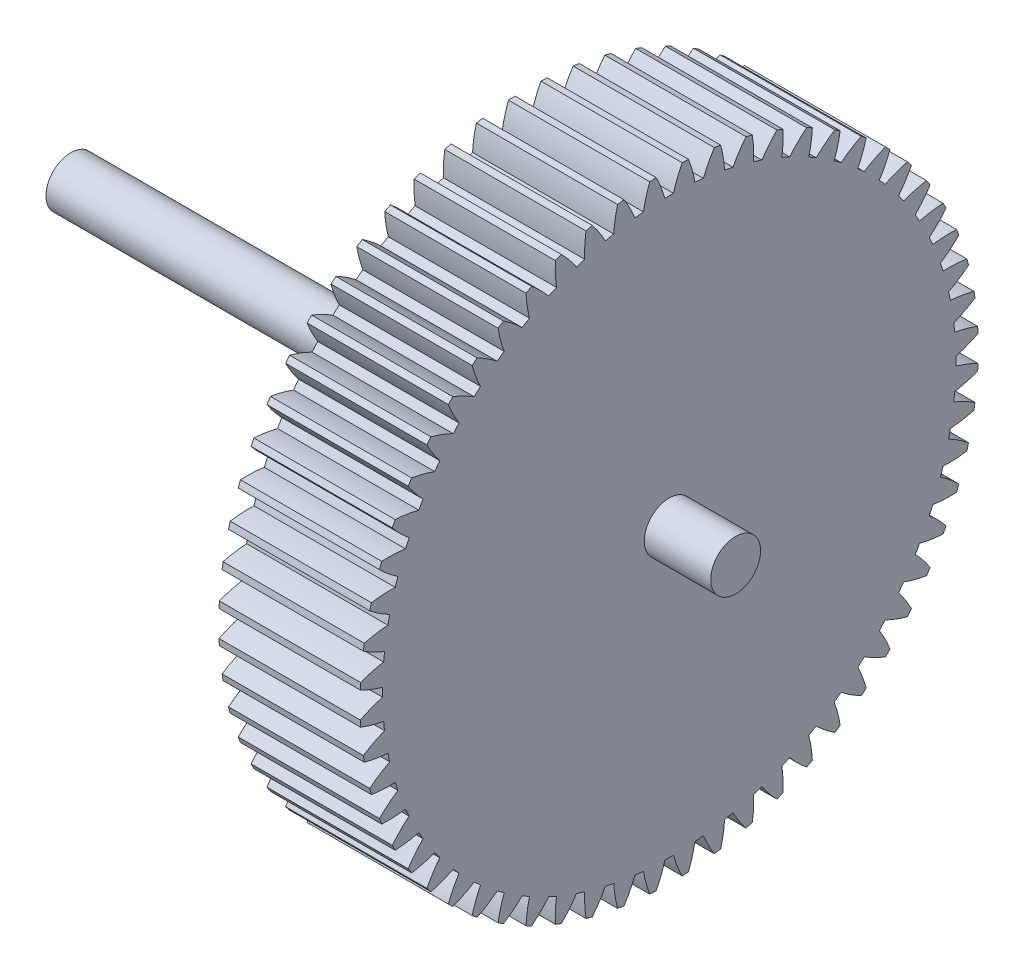
SolidWorks part; units mm, degrees
ref_plane "Plane1" through (0, 0, 0) normal (0, 0, 1) x (1, 0, 0)
ref_plane "Plane2" through (0, 0, 0) normal (0, 1, 0) x (1, 0, 0)
ref_plane "Plane3" through (0, 0, 0) normal (1, 0, 0) x (0, 0, -1)
sketch "HoldingSke" plane through (0, 0, 0) normal (0, 1, 0) x (1, 0, 0)
  line L0 (0, 0) -> (0.8333, -1.4434)
  line L1 (-15, 0) -> (100, 0) construction
  line L2 (0, 0) -> (-2.1039, 2.3779)
  line L3 (0, 0) -> (-11.863, 4.5341)
  line L4 (0, 0) -> (4.318, 7.479)
  line L5 (0, 0) -> (-46.8476, -17.4728)
  line L6 (0, 0) -> (-7.0462, -4.7541)
  line L7 (-2.1039, 2.3779) -> (8.6586, 51.2059)
  line L8 (-76.2, 54.61) -> (-75.9, 54.61)
  line L9 (-71.009, 38.7566) -> (-53.1078, 45.2721)
  line L10 (-76.2, 71.12) -> (104.1128, 71.12)
  line L11 (0, 0) -> (-8.5, 0)
  line L12 (-76.2, 101.6) -> (-76.177, 101.6)
  line L13 (24.9733, 27.94) -> (52.9518, 28.4284)
  line L14 (24.9733, 27.94) -> (24.9743, 27.94)
  line L15 (24.9733, 27.94) -> (100.4006, 29.5858)
  line L16 (-63.627, -0.6) -> (-12.827, -0.6)
  circle A0 centre (0, 0) radius 1
  circle A1 centre (0, 0) radius 17.249
  circle A2 centre (0, 0) radius 37.5
  circle A3 centre (0, 0) radius 1
  dimension "MHD" = 34.498
  dimension "Hub_dia" = 75
  dimension "Bore" = 2
  dimension "MBD" = 2
  dimension "Num_teeth" = 60
  dimension "Pitch" = 1.6667
  dimension "Overall_len" = 50
  dimension "Show_teeth" = 60
  dimension "Thickness" = 8.5
  dimension "OAL" = 50.0001
  dimension "T_dim" = 0.3
  dimension "Ap" = 20
  dimension "H" = 19.05
  dimension "Pitch_radius" = 180.3128
  dimension "Width" = 8.5
  dimension "Backlash" = 0.023
  dimension "Addendum_fac" = 1
  dimension "Dedendum_fac" = 1.25
  dimension "Clearance_fac" = 0.25
  dimension "Dedendum_add" = 0.001
  dimension "Module" = 0.6
sketch "BasProSke" plane through (0, 0, 0) normal (0, 1, 0) x (1, 0, 0)
  line L0 (-10, 0) -> (60, 0) construction
  line L1 (0, 0) -> (0, 18.6)
  line L2 (0, 0) -> (8.5, 0)
  line L3 (8.5, 0) -> (8.5, 18.6)
  line L4 (8.5, 18.6) -> (0, 18.6)
  dimension "Thickness" = 8.5
  dimension "Diameter" = 37.2
revolve "Base-Revolve" add sketch "BasProSke" angle 360 about L0
sketch "TooCutSke" plane through (0, 0, 0) normal (1, 0, 0) x (0, 0, -1)
  line L1 (0, 0) -> (0, 107) construction
  line L2 (0, 0) -> (-0.5114, 17.9927) construction
  line L3 (0, 0) -> (-1.8836, 35.9404) construction
  line L4 (-0.5114, 17.9927) -> (-0.9418, 17.9702) construction
  arc A0 (0.2583, 17.2471) -> (-0.2583, 17.2471) centre (0, 0) ccw
  arc A1 (0.7931, 18.6085) -> (-0.7931, 18.6085) centre (0, 0) ccw
  circle A2 centre (0, 0) radius 18 construction
  circle A3 centre (0, 0) radius 16.9145 construction
  arc A4 (-0.2583, 17.2471) -> (-0.7931, 18.6085) centre (-7.1926, 15.309) ccw
  arc A5 (0.7931, 18.6085) -> (0.2583, 17.2471) centre (7.1926, 15.309) ccw
  dimension "Root_dia" = 34.498
  dimension "Overcut_dia" = 37.2508
  dimension "Pitch_dia" = 36
  dimension "Base_dia" = 33.8289
  dimension "Flank_rad" = 7.2
  dimension "Half_ang" = 3
  dimension "Half_CT" = 0.4309
extrude "ToothCut" cut sketch "TooCutSke" along normal through all
fillet "Breaks" [suppressed] radius 0.012
fillet "RootFillets" [suppressed] radius 0.151
pattern_circular "TeethCuts" count 60 every 6 about axis through (-10, 0, 0) along (1, 0, 0) of "ToothCut", "RootFillets", "Breaks"
sketch "HubNeaOneSke" plane through (0, 0, 0) normal (-1, 0, 0) x (0, 0, 1)
  circle A0 centre (0, 0) radius 17.249
  dimension "Diameter" = 34.498
extrude "HubNearOne" [suppressed] add sketch "HubNeaOneSke" along normal blind 41.5001
sketch "HubNeaBotSke" plane through (0, 0, 0) normal (-1, 0, 0) x (0, 0, 1)
  circle A0 centre (0, 0) radius 17.249
  dimension "Diameter" = 34.498
extrude "HubNearBoth" [suppressed] add sketch "HubNeaBotSke" along normal blind 20.75
ref_plane "FarPln" through (8.5, 0, 0) normal (1, 0, 0) x (0, 0, -1)
sketch "HubFarSke" plane through (8.5, 0, 0) normal (1, 0, 0) x (0, 0, -1)
  circle A0 centre (0, 0) radius 17.249
  dimension "Diameter" = 34.498
extrude "HubFar" [suppressed] add sketch "HubFarSke" along normal blind 20.75
sketch "BorSke" plane through (0, 0, 0) normal (1, 0, 0) x (0, 0, -1)
  circle A0 centre (0, 0) radius 1
  dimension "Diameter" = 2
extrude "Bore" cut sketch "BorSke" along normal mid plane 100.0001
sketch "KeySke" plane through (0, 0, 0) normal (1, 0, 0) x (0, 0, -1)
  line L0 (-0.4, 0) -> (-0.4, 1.3)
  line L1 (-0.4, 1.3) -> (0.4, 1.3)
  line L2 (0.4, 1.3) -> (0.4, 0)
  line L3 (0, 0) -> (0, 34) construction
  line L4 (-0.4, 0) -> (0.4, 0)
  dimension "Offset" = 1.3
  dimension "Width" = 0.8
extrude "Keyway" [suppressed] cut sketch "KeySke" along normal mid plane 100.0001
pattern_circular "Keyway2" [suppressed] count 2 every 90 about axis through (-10, 0, 0) along (1, 0, 0)
sketch "Skizze1" plane through (8.5, 0, 0) normal (1, 0, 0) x (0, 0, -1)
  circle A0 centre (0, 0) radius 1.5
  dimension "D1" = 3
extrude "Aufsatz-Linear austragen1" add sketch "Skizze1" along normal blind 4 and the other way blind 36
equation "' \"Module@HoldingSke\" = 6.35"
equation "' \"Num_teeth@HoldingSke\" = 12"
equation "' \"Ap@HoldingSke\" =  20"
equation "' \"Ap@HoldingSke\" = 20"
equation "' \"Width@HoldingSke\" = 0.5 * 25.4"
equation "' \"Hub_dia@HoldingSke\"= 1 * 25.4"
equation "' \"Hub_dia@HoldingSke\" = 1 * 25.4"
equation "' \"Overall_len@HoldingSke\" = 1.0 * 25.4"
equation "' \"Bore@HoldingSke\" = 0.75 * 25.4"
equation "' \"T_dim@HoldingSke\" = 0.1 * 25.4"
equation "' \"Width@KeySke\" = 0.25 * 25.4"
equation "' \"Show_teeth@HoldingSke\" = 13"
equation "' \"Backlash@HoldingSke\" = 0.009 * 25.4"
equation "' \"Addendum_fac@HoldingSke\" = 1.0"
equation "' \"Dedendum_fac@HoldingSke\" = 1.25"
equation "' \"Dedendum_add@HoldingSke\" = 0.00005 * 25.4"
equation "' \"Clearance_fac@HoldingSke\" = 0.25"
equation "\"Pitch@HoldingSke\" = 1 / \"Module@HoldingSke\""
equation "\"Overcut_dia@TooCutSke\" = (\"Num_teeth@HoldingSke\" + 2 * \"Addendum_fac@HoldingSke\") / \"Pitch@HoldingSke\" + 0.002 * 25.4"
equation "\"Pitch_dia@TooCutSke\" = \"Num_teeth@HoldingSke\" / \"Pitch@HoldingSke\""
equation "\"Base_dia@TooCutSke\" = \"Num_teeth@HoldingSke\" / \"Pitch@HoldingSke\" * cos((\"Ap@HoldingSke\"  * 3.14159265 / 180))"
equation "\"Root_dia@TooCutSke\" = (\"Num_teeth@HoldingSke\" + 2) / \"Pitch@HoldingSke\" - 2 * (\"Addendum_fac@HoldingSke\" + \"Dedendum_fac@HoldingSke\") / \"Pitch@HoldingSke\" - \"Dedendum_add@HoldingSke\" * 2"
equation "\"Half_ang@TooCutSke\" = 180 / \"Num_teeth@HoldingSke\""
equation "\"Half_CT@TooCutSke\" = \"Num_teeth@HoldingSke\" / \"Pitch@HoldingSke\" * sin((3.14159265 / 2 / \"Num_teeth@HoldingSke\")) / 2 - 7 * \"Backlash@HoldingSke\" / 4"
equation "\"Flank_rad@TooCutSke\" = \"Num_teeth@HoldingSke\" / \"Pitch@HoldingSke\" / 5"
equation "\"Radius@RootFillets\" = \"Clearance_fac@HoldingSke\" / \"Pitch@HoldingSke\" + \"Dedendum_add@HoldingSke\""
equation "\"Break_rad@Breaks\" = 0.02 / \"Pitch@HoldingSke\""
equation "\"Thickness@HoldingSke\" = \"Width@HoldingSke\""
equation "\"OAL@HoldingSke\" = \"Thickness@HoldingSke\""
equation "\"MHD@HoldingSke\" = (\"Num_teeth@HoldingSke\" + 2) / \"Pitch@HoldingSke\" - 2 * (\"Addendum_fac@HoldingSke\" + \"Dedendum_fac@HoldingSke\")  / \"Pitch@HoldingSke\" - \"Dedendum_add@HoldingSke\" * 2"
equation "\"MBD@HoldingSke\" = (\"Num_teeth@HoldingSke\" + 2) / \"Pitch@HoldingSke\" - 2 * (\"Addendum_fac@HoldingSke\" + \"Dedendum_fac@HoldingSke\")  / \"Pitch@HoldingSke\" - \"Dedendum_add@HoldingSke\" * 2 - 0.002 * 25.4"
equation "\"MHD@HoldingSke\" = ((sgn( \"MHD@HoldingSke\" - \"Hub_dia@HoldingSke\" )-1)*( \"MHD@HoldingSke\" - \"Hub_dia@HoldingSke\" ))/-2+ \"Hub_dia@HoldingSke\""
equation "\"MBD@HoldingSke\" = ((sgn( \"MBD@HoldingSke\" - \"Bore@HoldingSke\" )-1)*( \"MBD@HoldingSke\" - \"Bore@HoldingSke\" ))/-2+ \"Bore@HoldingSke\""
equation "\"OAL@HoldingSke\" = ((sgn( \"OAL@HoldingSke\" - \"Overall_len@HoldingSke\" )+1)*( \"OAL@HoldingSke\" - \"Overall_len@HoldingSke\" ))/2 + \"Overall_len@HoldingSke\" + 0.000002 * 25.4"
equation "\"Num_teeth@TeethCuts\" = int( \"Show_teeth@HoldingSke\" ) + 1"
equation "\"Num_teeth@TeethCuts\" = ((sgn( \"Num_teeth@TeethCuts\" - \"Num_teeth@HoldingSke\" )-1)*( \"Num_teeth@TeethCuts\" - \"Num_teeth@HoldingSke\" ))/-2+ \"Num_teeth@HoldingSke\""
equation "\"Num_teeth@TeethCuts\" = ((sgn( \"Num_teeth@TeethCuts\" - 2.0)+1)*( \"Num_teeth@TeethCuts\" - 2.0))/2 +2.0"
equation "\"Angle@TeethCuts\" = 360.0 / \"Num_teeth@HoldingSke\""
equation "\"Diameter@BasProSke\" = (\"Num_teeth@HoldingSke\" + 2 * \"Addendum_fac@HoldingSke\") / \"Pitch@HoldingSke\""
equation "\"Thickness@BasProSke\"  = \"Thickness@HoldingSke\""
equation "' \"Fillet_rad@BasProSke\" =  \"Thickness@HoldingSke\" * 0.05"
equation "' \"Fillet_rad@BasProSke\" = \"Thickness@HoldingSke\" * 0.05"
equation "\"MHD@HoldingSke\" = ((sgn( \"MHD@HoldingSke\" - \"Root_dia@TooCutSke\" )-1)*( \"MHD@HoldingSke\" - \"Root_dia@TooCutSke\" ))/-2+ \"Root_dia@TooCutSke\""
equation "\"Diameter@HubNeaOneSke\" = \"MHD@HoldingSke\""
equation "\"Length@HubNearOne\" = \"OAL@HoldingSke\" - \"Thickness@BasProSke\""
equation "\"Diameter@HubNeaBotSke\" = \"MHD@HoldingSke\""
equation "\"Length@HubNearBoth\" = ( \"OAL@HoldingSke\" - \"Thickness@BasProSke\" ) / 2.0"
equation "\"Thickness@FarPln\" = \"Thickness@BasProSke\""
equation "\"Diameter@HubFarSke\" = \"MHD@HoldingSke\""
equation "\"Length@HubFar\" = ( \"OAL@HoldingSke\" - \"Thickness@BasProSke\" ) / 2.0"
equation "\"Diameter@BorSke\" = \"MBD@HoldingSke\""
equation "\"D1@Bore\" = \"OAL@HoldingSke\" * 2.0"
equation "\"D1@Keyway\" = \"OAL@HoldingSke\" * 2.0"
equation "\"Offset@KeySke\" = \"T_dim@HoldingSke\" + \"MBD@HoldingSke\" / 2.0"
